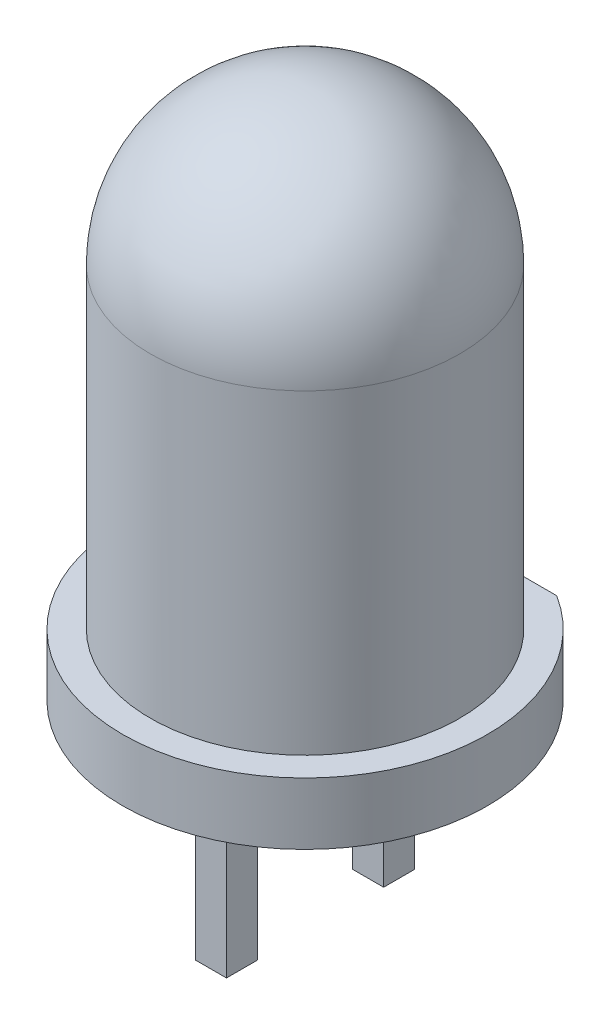
SolidWorks part; units mm, degrees
ref_plane "Front Plane" through (0, 0, 0) normal (0, 0, 1) x (1, 0, 0)
ref_plane "Top Plane" through (0, 0, 0) normal (0, 1, 0) x (1, 0, 0)
ref_plane "Right Plane" through (0, 0, 0) normal (1, 0, 0) x (0, 0, -1)
sketch "Sketch1" plane through (0, 0, 0) normal (0, 1, 0) x (1, 0, 0)
  circle A0 centre (0, 0) radius 2.95
  dimension "D1" = 5.9
extrude "Boss-Extrude1" add sketch "Sketch1" along normal blind 1
sketch "Sketch2" plane through (0, 1, 0) normal (0, 1, 0) x (1, 0, 0)
  circle A0 centre (0, 0) radius 2.5
  dimension "D1" = 5
extrude "Boss-Extrude2" add sketch "Sketch2" along normal blind 7.6
sketch "Sketch3" plane through (0, 1, 0) normal (0, 1, 0) x (1, 0, 0)
  line L0 (-1.566, 2.5) -> (1.566, 2.5)
  circle A2 centre (0, 0) radius 2.95 construction
  arc A3 (-1.566, 2.5) -> (1.566, 2.5) centre (0, 0) cw
  point P3 (0, 2.5)
  circle M2 centre (0, 0) radius 2.95
extrude "Cut-Extrude1" cut sketch "Sketch3" against normal blind 7.6 contours L0 M2
fillet "Fillet1" radius 2.5 1 edges at (0, 8.6, 2.5)
sketch "Sketch4" plane through (0, 0, 0) normal (0, -1, 0) x (1, 0, 0)
  line L0 (0, 2.95) -> (0, -2.5) construction
  line L2 (-0.25, 1.52) -> (0.25, 1.52)
  line L3 (-0.25, 1.52) -> (-0.25, 1.02)
  line L4 (-0.25, 1.02) -> (0.25, 1.02)
  line L5 (0.25, 1.52) -> (0.25, 1.02)
  line L6 (-0.25, 1.52) -> (0.25, 1.02) construction
  line L7 (-0.25, 1.02) -> (0.25, 1.52) construction
  line L8 (-0.25, -1.02) -> (0.25, -1.02)
  line L9 (-0.25, -1.02) -> (-0.25, -1.52)
  line L10 (-0.25, -1.52) -> (0.25, -1.52)
  line L11 (0.25, -1.02) -> (0.25, -1.52)
  line L12 (-0.25, -1.02) -> (0.25, -1.52) construction
  line L13 (-0.25, -1.52) -> (0.25, -1.02) construction
  arc A0 (1.566, -2.5) -> (-1.566, -2.5) centre (0, 0) ccw construction
  point P6 (0, 1.27)
  point P11 (0, -1.27)
  dimension "D1" = 0.5
  dimension "D2" = 0.5
  dimension "D3" = 0.5
  dimension "D4" = 0.5
  dimension "D5" = 1.27
  dimension "D6" = 1.27
extrude "Boss-Extrude3" add sketch "Sketch4" along normal blind 3
